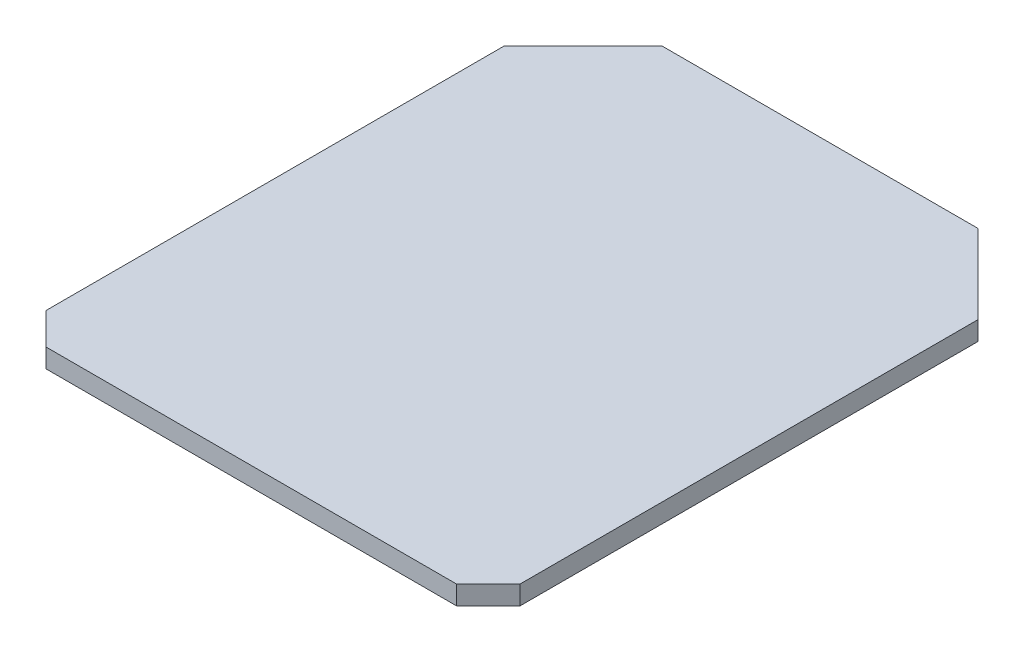
SolidWorks part; units mm, degrees
ref_plane "Front" through (0, 0, 0) normal (0, 0, 1) x (1, 0, 0)
ref_plane "Top" through (0, 0, 0) normal (0, 1, 0) x (1, 0, 0)
ref_plane "Right" through (0, 0, 0) normal (1, 0, 0) x (0, 0, -1)
sketch "Sketch5" plane through (0, 0, 0) normal (0, 1, 0) x (1, 0, 0)
  line L0 (0, 155) -> (25, 180)
  line L1 (10, 0) -> (140, 0)
  line L2 (0, 10) -> (0, 155)
  line L3 (25, 180) -> (125, 180)
  line L4 (150, 10) -> (150, 155)
  line L5 (125, 180) -> (150, 155)
  line L6 (0, 10) -> (10, 0)
  line L7 (140, 0) -> (150, 10)
  point P0 (0, 0)
  point P1 (150, 180)
  point P2 (0, 180)
  point P3 (150, 0)
  dimension "D1" = 150
  dimension "D2" = 180
  dimension "D3" = 25
  dimension "D4" = 25
  dimension "D5" = 25
  dimension "D6" = 25
  dimension "D7" = 10
  dimension "D8" = 10
  dimension "D9" = 10
  dimension "D10" = 10
extrude "Boss-Extrude1" add sketch "Sketch5" along normal blind 6
